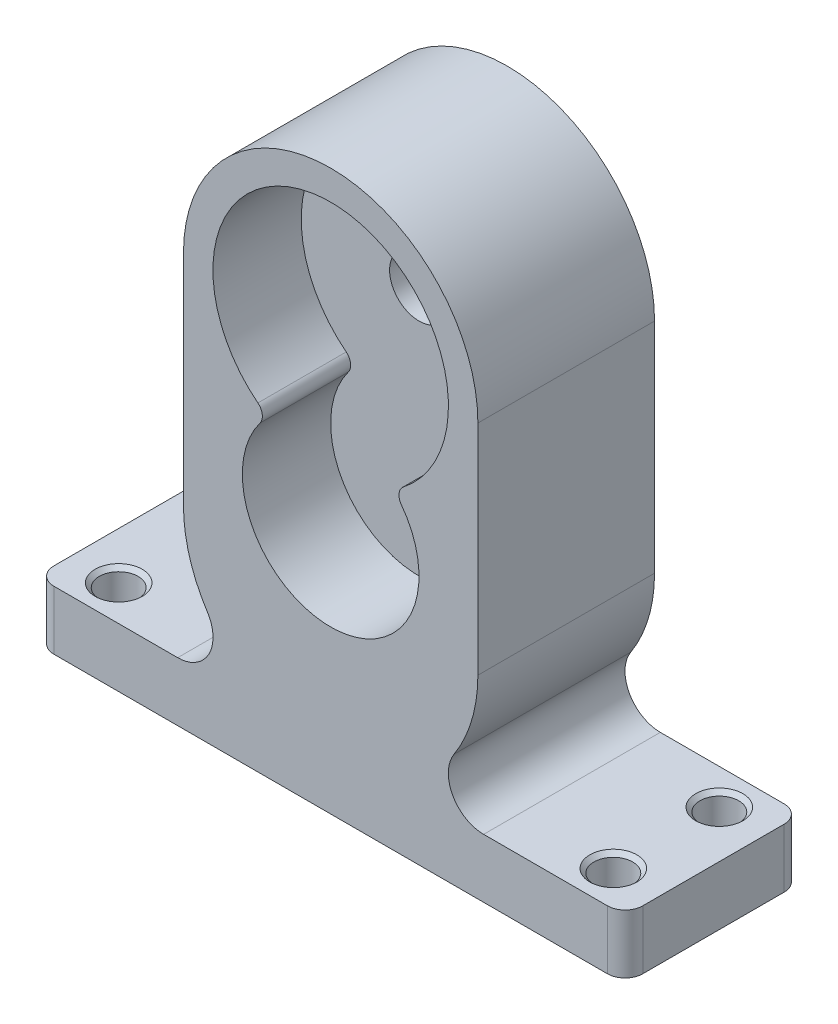
SolidWorks part; units mm, degrees
ref_plane "Спереди" through (0, 0, 0) normal (0, 0, 1) x (1, 0, 0)
ref_plane "Сверху" through (0, 0, 0) normal (0, 1, 0) x (1, 0, 0)
ref_plane "Справа" through (0, 0, 0) normal (1, 0, 0) x (0, 0, -1)
sketch "Эскиз1" plane through (0, 0, 0) normal (0, 0, 1) x (1, 0, 0)
  line L1 (0, 10) -> (0, 0)
  line L2 (0, 0) -> (50, 0)
  line L3 (50, 0) -> (50, 10)
  line L4 (50, 10) -> (10, 10)
  line L5 (25, 70.0002) -> (25, 32.9129)
  line L6 (0, 32.9129) -> (0, 10)
  line L7 (0, 95.0002) -> (0, 32.9129)
  arc A2 (0, 95.0002) -> (25, 70.0002) centre (0, 70.0002) cw
  arc A3 (10, 10) -> (25, 32.9129) centre (0, 32.9129) ccw
  dimension "D4" = 10
  dimension "D5" = 25
  dimension "D1" = 10
  dimension "D3" = 50
  dimension "D6" = 70.0002
extrude "Бобышка-Вытянуть1" add sketch "Эскиз1" against normal blind 30
mirror "Зеркальное отражение1" about plane through (0, 95.0002, -30) normal (-1, 0, 0) of "Бобышка-Вытянуть1"
sketch "Эскиз2" plane through (0, 0, 0) normal (0, 0, 1) x (1, 0, 0)
  circle A0 centre (0, 70.0002) radius 20
  arc A2 (25, 70.0002) -> (-25, 70.0002) centre (0, 70.0002) ccw construction
  dimension "D1" = 40
extrude "Вырез-Вытянуть1" cut sketch "Эскиз2" against normal blind 15
sketch "Эскиз3" plane through (0, 0, -15) normal (0, 0, 1) x (1, 0, 0)
  circle A0 centre (0, 70.0002) radius 5
  arc A1 (25, 70.0002) -> (-25, 70.0002) centre (0, 70.0002) ccw construction
  dimension "D1" = 10
extrude "Вырез-Вытянуть2" cut sketch "Эскиз3" against normal through all
fillet "Скругление5" radius 6 2 edges at (-10, 10, -15) (10, 10, -15)
sketch "Эскиз4" plane through (0, 0, 0) normal (0, 0, 1) x (1, 0, 0)
  circle A0 centre (0, 42.5) radius 15
  dimension "D1" = 42.5
  dimension "D2" = 30
extrude "Вырез-Вытянуть3" cut sketch "Эскиз4" against normal blind 15
fillet "Скругление6" radius 2 2 edges at (10.6448, 53.0683, -7.5) (-10.6448, 53.0683, -7.5)
sketch "Эскиз7" plane through (0, 10, 0) normal (0, 1, 0) x (1, 0, 0)
  line L0 (50, 30) -> (50, 0) construction
  line L1 (50, 30) -> (25.9799, 30) construction
  point P0 (42, 24)
  dimension "D1" = 8
  dimension "D2" = 6
hole_wizard "Зенковка для винта с полупотайной головкой M62" positions "Трехмерный эскиз2" profile "Эскиз8" countersink size "M6" standard "ISO" end condition through all
sketch3d "Трехмерный эскиз2"
  point P0 (42, 10, -24)
sketch "Эскиз8" plane through (42, 10, -24) normal (1, 0, 0) x (0, 0, 1)
  line L0 (0, 0) -> (0, 10)
  line L1 (0, 10) -> (3.3, 10)
  line L2 (3.3, 10) -> (3.3, 0.7)
  line L3 (3.3, 0.7) -> (4, 0)
  line L5 (4, 0) -> (0, 0)
  line L6 (-3.3, 0.7) -> (-4, 0) construction
  line L11 (0, -6.35) -> (0, 107.95) construction
  dimension "Диаметр сквозного отверстия" = 6.6
  dimension "Глубина сквозного отверстия" = 10
  dimension "Диаметр передней зенковки" = 8
  dimension "Угол передней зенковки" = 90
pattern_linear "Линейный массив1" count 2 spacing 18 along (0, 0, 1) count 2 spacing 84 along (-1, 0, 0) of "Зенковка для винта с полупотайной головкой M62"
fillet "Скругление7" radius 3 4 edges at (-50, 5, 0) (-50, 5, -30) (50, 5, -30) (50, 5, 0)
